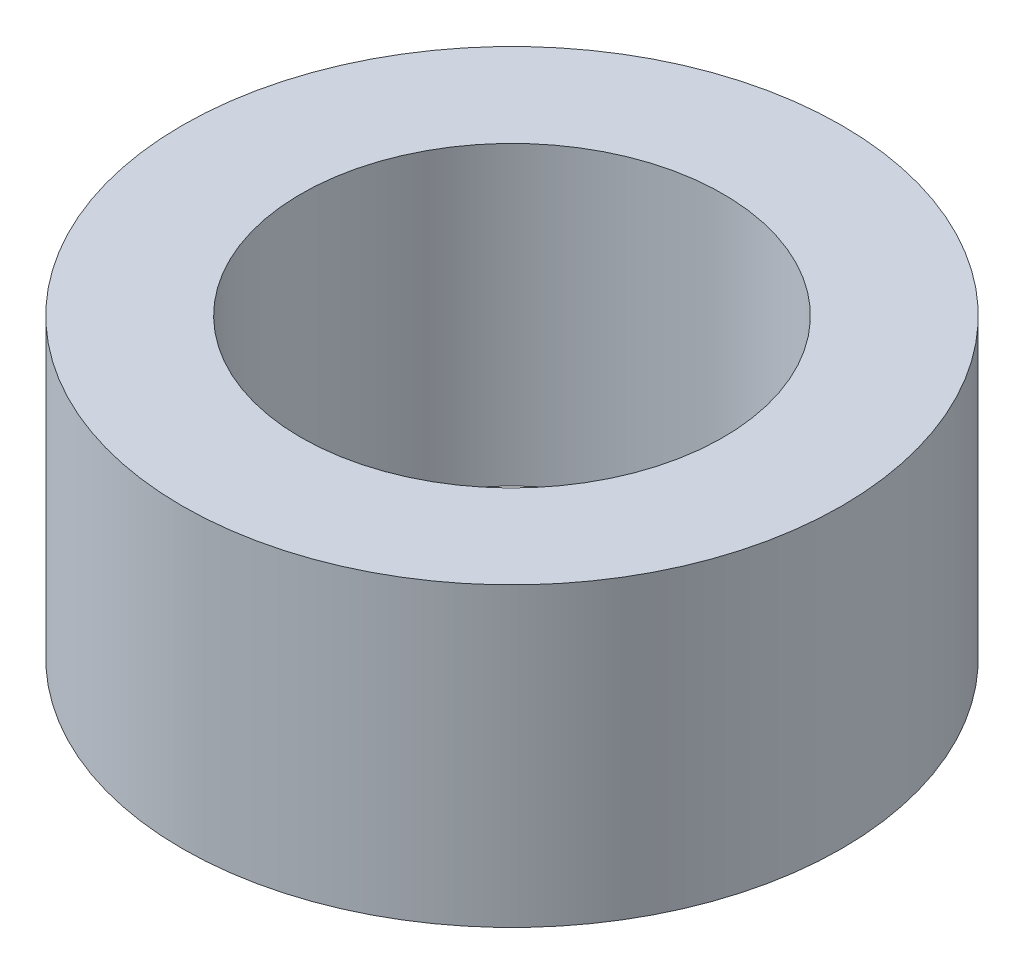
SolidWorks part; units mm, degrees
ref_plane "前视基准面" through (0, 0, 0) normal (0, 0, 1) x (1, 0, 0)
ref_plane "上视基准面" through (0, 0, 0) normal (0, 1, 0) x (1, 0, 0)
ref_plane "右视基准面" through (0, 0, 0) normal (1, 0, 0) x (0, 0, -1)
sketch "草图1" plane through (0, 0, 0) normal (0, 1, 0) x (1, 0, 0)
  circle A0 centre (0, 0) radius 3.2
  circle A1 centre (0, 0) radius 5
  dimension "D1" = 6.4
  dimension "D2" = 10
extrude "凸台-拉伸1" add sketch "草图1" along normal blind 4.5
